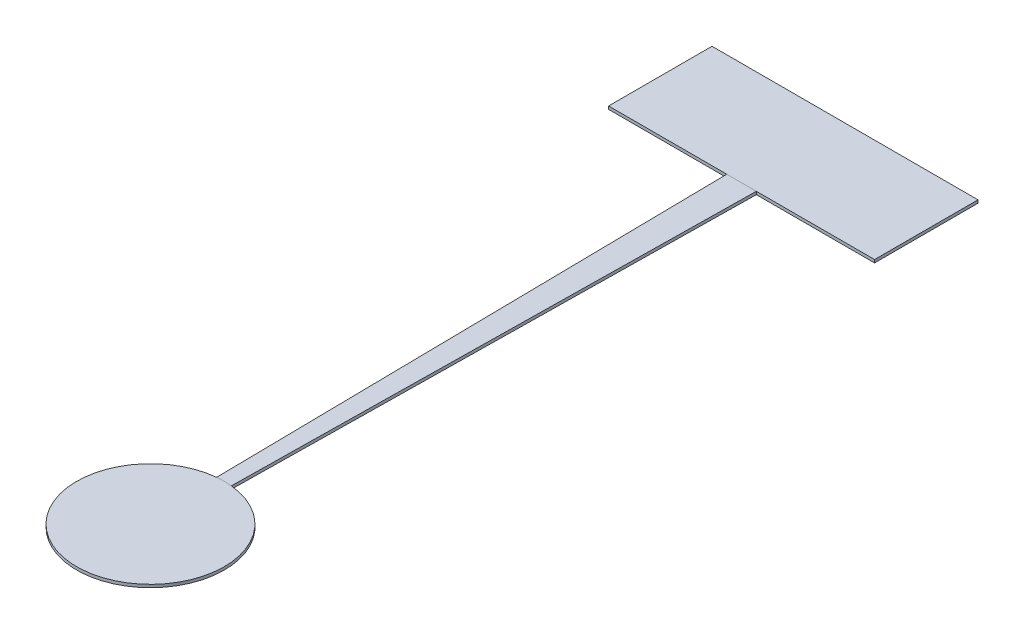
SolidWorks part; units mm, degrees
material "AISI 304"
ref_plane "前视基准面" through (0, 0, 0) normal (0, 0, 1) x (1, 0, 0)
ref_plane "上视基准面" through (0, 0, 0) normal (0, 1, 0) x (1, 0, 0)
ref_plane "右视基准面" through (0, 0, 0) normal (1, 0, 0) x (0, 0, -1)
sketch "草图1" plane through (0, 0, 0) normal (0, 1, 0) x (1, 0, 0)
  line L0 (0, -3.5) -> (0, -43.5) construction
  line L1 (9, -3.5) -> (1, -3.5)
  line L2 (9, -3.5) -> (9, 3.5)
  line L3 (9, 3.5) -> (-9, 3.5)
  line L4 (-9, -3.5) -> (-9, 3.5)
  line L5 (9, -3.5) -> (-9, 3.5) construction
  line L6 (9, 3.5) -> (-9, -3.5) construction
  line L7 (-1, -3.5) -> (-0.5, -38.5251)
  line L8 (1, -3.5) -> (0.5, -38.5251)
  line L9 (-1, -3.5) -> (-9, -3.5)
  arc A0 (-0.5, -38.5251) -> (0.5, -38.5251) centre (0, -43.5) ccw
  point P0 (0, 0)
  dimension "D4" = 10
  dimension "D1" = 18
  dimension "D2" = 7
  dimension "D3" = 40
  dimension "D5" = 1
  dimension "D6" = 0.5
extrude "凸台-拉伸1" add sketch "草图1" along normal blind 0.2
sketch "草图2" plane through (0, 0.2, 0) normal (0, 1, 0) x (1, 0, 0)
  line L0 (-1, -3.5) -> (1, -3.5)
split line "分割线1"
sketch "草图3" plane through (0, 0.2, 0) normal (0, 1, 0) x (1, 0, 0)
  line L0 (-1, -3.5) -> (-0.5, -38.5251) construction
  arc A0 (-0.5, -38.5251) -> (0.5, -38.5251) centre (0, -43.5) ccw construction
  arc A1 (-0.5, -38.5251) -> (0.5, -38.5251) centre (0, -43.5) cw
split line "分割线2"
